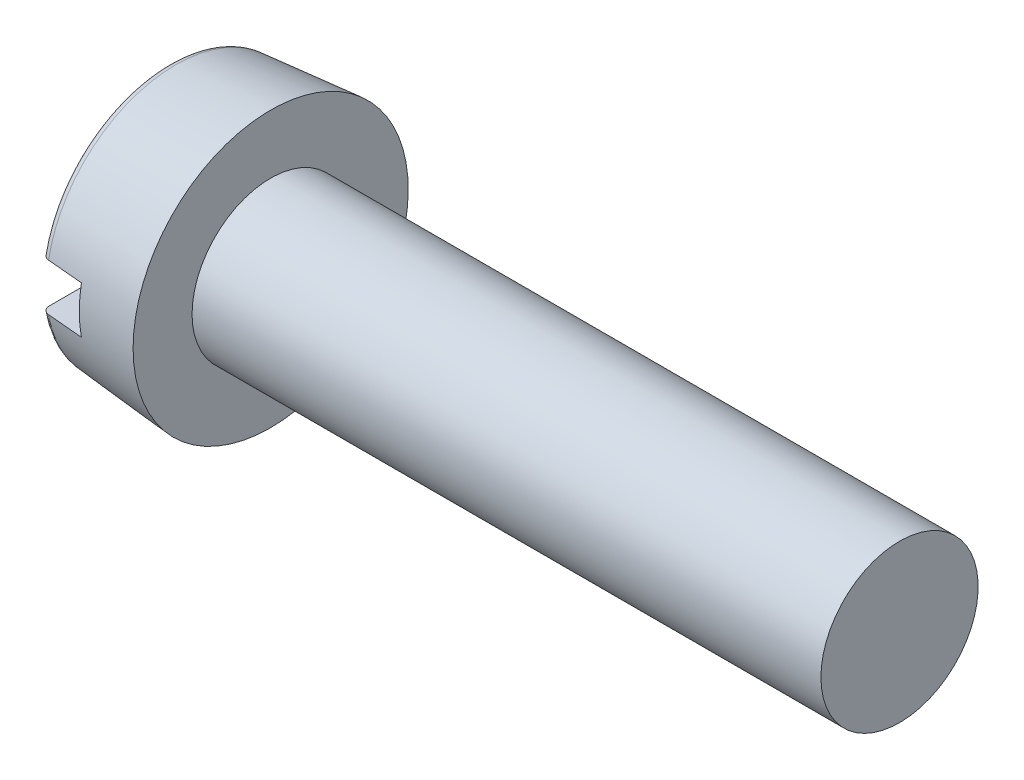
SolidWorks part; units mm, degrees
ref_plane "Plane1" through (0, 0, 0) normal (0, 0, 1) x (1, 0, 0)
ref_plane "Plane2" through (0, 0, 0) normal (0, 1, 0) x (1, 0, 0)
ref_plane "Plane3" through (0, 0, 0) normal (1, 0, 0) x (0, 0, -1)
sketch "BodySke" plane through (0, 0, 0) normal (0, 0, 1) x (1, 0, 0)
  line L0 (2.6, 2) -> (2.6, 3.5)
  line L1 (0, 0) -> (0, 3.2725)
  line L2 (-25.4, 0) -> (127, 0) construction
  line L3 (18.6, 0) -> (0, 0)
  line L4 (2.6, 2) -> (18.6, 2)
  line L5 (18.6, 2) -> (18.6, 0)
  line L6 (0, 3.2725) -> (2.6, 3.5)
  line L9 (3.3, 3.5875) -> (3.3, -5.9375) construction
  line L10 (2.6, 6.35) -> (2.6, -3.175) construction
  dimension "Length" = 16
  dimension "Head_ht" = 2.6
  dimension "Advance" = 0.7
  dimension "Thread_nom" = 16
  dimension "Head_dia" = 7
  dimension "Head_side_angle" = 5
  dimension "Diameter" = 4
revolve "Base-Revolve" add sketch "BodySke"
cosmetic thread "ThreadCosmetic" [suppressed]
fillet "Fillet1" [suppressed] radius 0.2
fillet "Fillet2" radius 0.2 1 edges at (0, 0, 3.2725)
sketch "Sketch2" plane through (0, 0, 0) normal (1, 0, 0) x (0, 0, -1)
  line L0 (3.5, -0.6) -> (-3.5, -0.6)
  line L1 (3.5, -0.6) -> (3.5, 0.6)
  line L2 (-3.5, 0.6) -> (3.5, 0.6)
  line L3 (-3.5, 0.6) -> (-3.5, -0.6)
  dimension "D1" = 7
  dimension "Slot_width" = 1.2
  dimension "D2" = 3.5
  dimension "D3" = 0.6
extrude "Slot" cut sketch "Sketch2" along normal blind 1.1
sketch "ThdSchSke" plane through (0, 0, 0) normal (0, 0, 1) x (1, 0, 0)
  line L0 (4, -1.61) -> (3.7269, -2)
  line L1 (4, -1.61) -> (4.2731, -2)
  line L2 (4.2731, -2) -> (4.2731, -2.5)
  line L3 (-3.175, 0) -> (5.1513, 0) construction
  line L5 (4.2731, -2.5) -> (3.7269, -2.5)
  line L6 (3.7269, -2.5) -> (3.7269, -2)
  dimension "Diameter" = 4
  dimension "SideAngle" = 55
  dimension "VeeAngle" = 70
  dimension "Thread_minor" = 3.22
  dimension "Overcut" = 5
  dimension "Start" = 4
revolve "ThreadSchematic" [suppressed] cut sketch "ThdSchSke" angle 360 about L3
pattern_linear "ThdSchPat" [suppressed]
equation "\"D1@Sketch2\" = \"Head_dia@BodySke\""
equation "\"D2@Sketch2\" = \"D1@Sketch2\" / 2"
equation "\"D3@Sketch2\" = \"Slot_width@Sketch2\" / 2"
equation "\"Thread_length@ThreadCosmetic\" = ((sgn( (\"Length@BodySke\" - \"Advance@BodySke\" * 2.0 ) - \"Thread_nom@BodySke\" )-1)*( (\"Length@BodySke\" - \"Advance@BodySke\"  * 2.0) - \"Thread_nom@BodySke\" ))/-2+ \"Thread_nom@BodySke\""
equation "\"Thread_minor@ThdSchSke\" = \"Thread_minor@ThreadCosmetic\""
equation "\"Diameter@ThdSchSke\" = \"Diameter@BodySke\""
equation "\"Overcut@ThdSchSke\" = \"Diameter@BodySke\" * 1.25"
equation "\"Start@ThdSchSke\" = \"Head_ht@BodySke\" + \"Length@BodySke\" - \"Thread_length@ThreadCosmetic\"  '---Non-countersunk---"
equation "\"Num_threads@ThdSchPat\" = int( \"Thread_length@ThreadCosmetic\" / \"Advance@BodySke\" + 0.999 )  + 1"
equation "\"Advance@ThdSchPat\" = \"Thread_length@ThreadCosmetic\" /  (\"Num_threads@ThdSchPat\" - 1) 'relax it"
